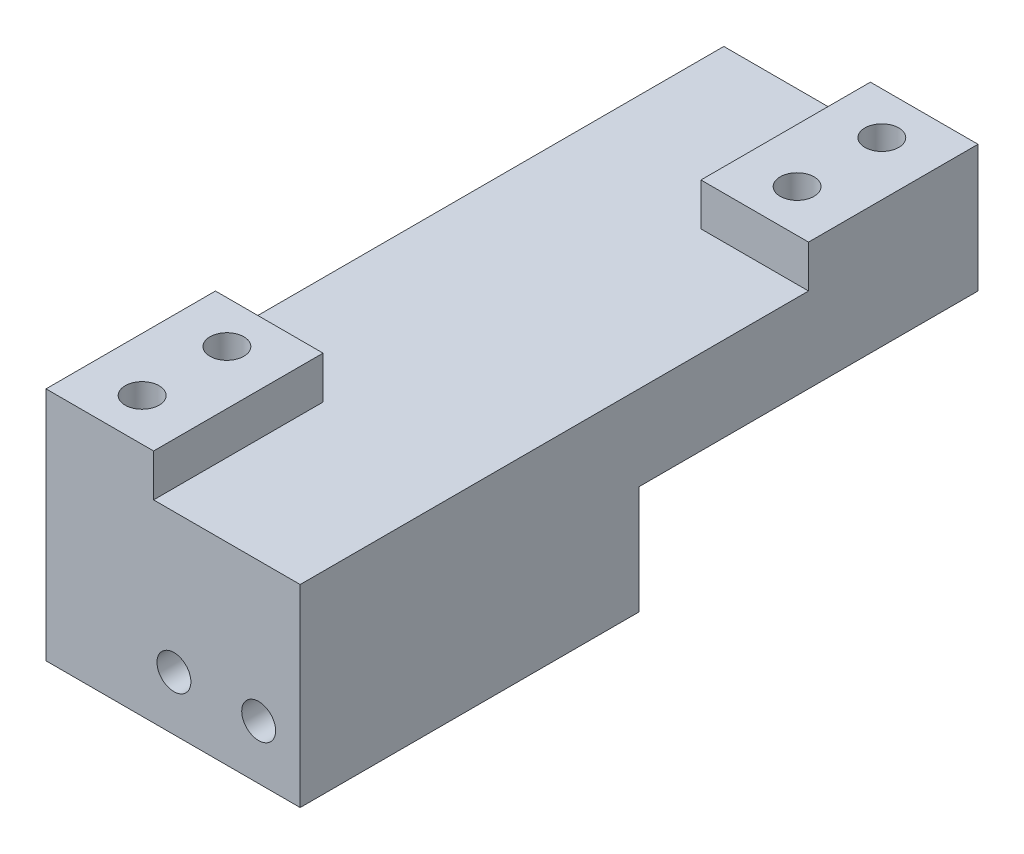
SolidWorks part; units mm, degrees
ref_plane "Front Plane" through (0, 0, 0) normal (0, 0, 1) x (1, 0, 0)
ref_plane "Top Plane" through (0, 0, 0) normal (0, 1, 0) x (1, 0, 0)
ref_plane "Right Plane" through (0, 0, 0) normal (1, 0, 0) x (0, 0, -1)
sketch "Sketch1" plane through (0, 0, 0) normal (0, 1, 0) x (1, 0, 0)
  line L1 (0, 0) -> (-30, 0)
  line L2 (0, 0) -> (0, 80)
  line L3 (0, 80) -> (-30, 80)
  line L4 (-30, 0) -> (-30, 80)
  dimension "D1" = 80
  dimension "D2" = 30
extrude "Boss-Extrude1" add sketch "Sketch1" along normal blind 30
sketch "Sketch2" plane through (0, 30, 0) normal (0, 1, 0) x (1, 0, 0)
  line L1 (-30, 0) -> (-17.3, 0)
  line L2 (-30, 0) -> (-30, 20)
  line L3 (-30, 20) -> (-17.3, 20)
  line L4 (-17.3, 0) -> (-17.3, 20)
  line L5 (0, 80) -> (-12.7, 80)
  line L6 (0, 80) -> (0, 60)
  line L7 (0, 60) -> (-12.7, 60)
  line L8 (-12.7, 80) -> (-12.7, 60)
  circle A0 centre (-23.65, 5) radius 2
  circle A1 centre (-23.65, 15) radius 2
  circle A2 centre (-6.35, 65) radius 2
  circle A3 centre (-6.35, 75) radius 2
  dimension "D5" = 4
  dimension "D6" = 4
  dimension "D7" = 4
  dimension "D8" = 4
  dimension "D1" = 20
  dimension "D2" = 12.7
  dimension "D3" = 12.7
  dimension "D4" = 20
  dimension "D9" = 6.35
  dimension "D10" = 10
  dimension "D11" = 5
  dimension "D12" = 6.35
  dimension "D13" = 6.35
  dimension "D14" = 6.35
  dimension "D15" = 5
  dimension "D16" = 10
extrude "Boss-Extrude2" add sketch "Sketch2" along normal blind 5
sketch "Sketch3" plane through (0, 35, 0) normal (0, 1, 0) x (1, 0, 0)
  circle A0 centre (-23.65, 15) radius 2
  circle A1 centre (-23.65, 5) radius 2
  circle A2 centre (-6.35, 75) radius 2
  circle A3 centre (-6.35, 65) radius 2
  dimension "D1" = 4
  dimension "D2" = 4
  dimension "D3" = 4
  dimension "D4" = 4
extrude "Cut-Extrude1" cut sketch "Sketch3" against normal through all
sketch "Sketch4" plane through (0, 0, -80) normal (0, 0, -1) x (-1, 0, 0)
  line L0 (0, 0) -> (30, 0) construction
  line L1 (0, 20) -> (20, 20)
  line L2 (0, 20) -> (0, 0)
  line L3 (0, 0) -> (20, 0)
  line L4 (20, 20) -> (20, 0)
  line L5 (0, 35) -> (0, 0) construction
  dimension "D1" = 20
  dimension "D2" = 0
  dimension "D3" = 20
extrude "Cut-Extrude2" cut sketch "Sketch4" against normal blind 40
sketch "Sketch5" plane through (0, 0, -80) normal (0, 0, -1) x (-1, 0, 0)
  line L0 (20, 20) -> (0, 20) construction
  line L1 (20, 0) -> (20, 20) construction
  line L2 (30, 30) -> (30, 0) construction
  line L3 (0, 0) -> (30, 0)
  line L4 (0, 0) -> (0, 7.2)
  line L5 (0, 7.2) -> (30, 7.2)
  line L6 (30, 0) -> (30, 7.2)
  circle A0 centre (4.9, 13.6) radius 2
  circle A1 centre (14.9, 13.6) radius 2
  dimension "D1" = 4
  dimension "D2" = 4
  dimension "D3" = 6.4
  dimension "D4" = 5.1
  dimension "D5" = 10
  dimension "D6" = 12.8
extrude "Cut-Extrude3" cut sketch "Sketch5" against normal through all
